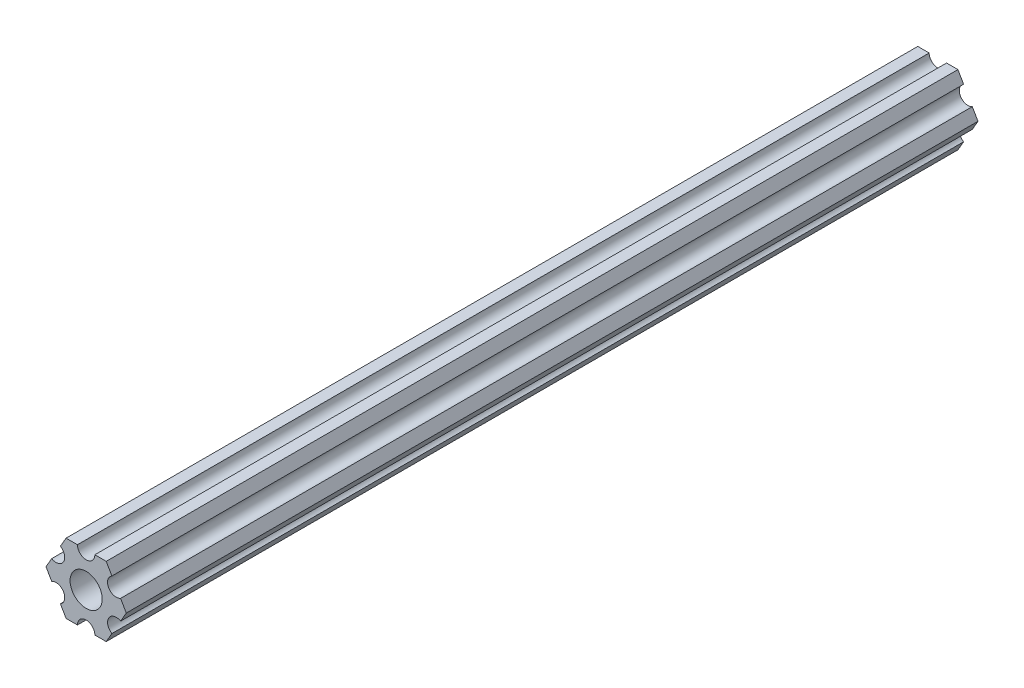
SolidWorks part; units mm, degrees
ref_plane "Front Plane" through (0, 0, 0) normal (0, 0, 1) x (1, 0, 0)
ref_plane "Top Plane" through (0, 0, 0) normal (0, 1, 0) x (1, 0, 0)
ref_plane "Right Plane" through (0, 0, 0) normal (1, 0, 0) x (0, 0, -1)
ref_plane "Plane1" through (0, 0, 304.8) normal (0, 0, 1) x (1, 0, 0)
sketch "Sketch1" plane through (0, 0, 304.8) normal (0, 0, 1) x (1, 0, 0)
  line L0 (6.293, -1.8002) -> (7.3323, 0)
  line L1 (7.3323, 0) -> (6.293, 1.8002)
  line L2 (4.7055, 4.5498) -> (3.6662, 6.35)
  line L3 (3.6662, 6.35) -> (1.5875, 6.35)
  line L4 (-1.5875, 6.35) -> (-3.6662, 6.35)
  line L5 (-3.6662, 6.35) -> (-4.7055, 4.5498)
  line L6 (-6.293, 1.8002) -> (-7.3323, 0)
  line L7 (-7.3323, 0) -> (-6.293, -1.8002)
  line L8 (-4.7055, -4.5498) -> (-3.6662, -6.35)
  line L9 (-3.6662, -6.35) -> (-1.5875, -6.35)
  line L10 (1.5875, -6.35) -> (3.6662, -6.35)
  line L11 (3.6662, -6.35) -> (4.7055, -4.5498)
  arc A0 (6.293, 1.8002) -> (4.7055, 4.5498) centre (5.4993, 3.175) cw
  arc A1 (1.5875, 6.35) -> (-1.5875, 6.35) centre (0, 6.35) cw
  arc A2 (-4.7055, 4.5498) -> (-6.293, 1.8002) centre (-5.4993, 3.175) cw
  arc A3 (-6.293, -1.8002) -> (-4.7055, -4.5498) centre (-5.4993, -3.175) cw
  arc A4 (-1.5875, -6.35) -> (1.5875, -6.35) centre (0, -6.35) cw
  arc A5 (4.7055, -4.5498) -> (6.293, -1.8002) centre (5.4993, -3.175) cw
  circle A6 centre (0, 0) radius 2.9337
extrude "Boss-Extrude1" add sketch "Sketch1" against normal blind 155.575
